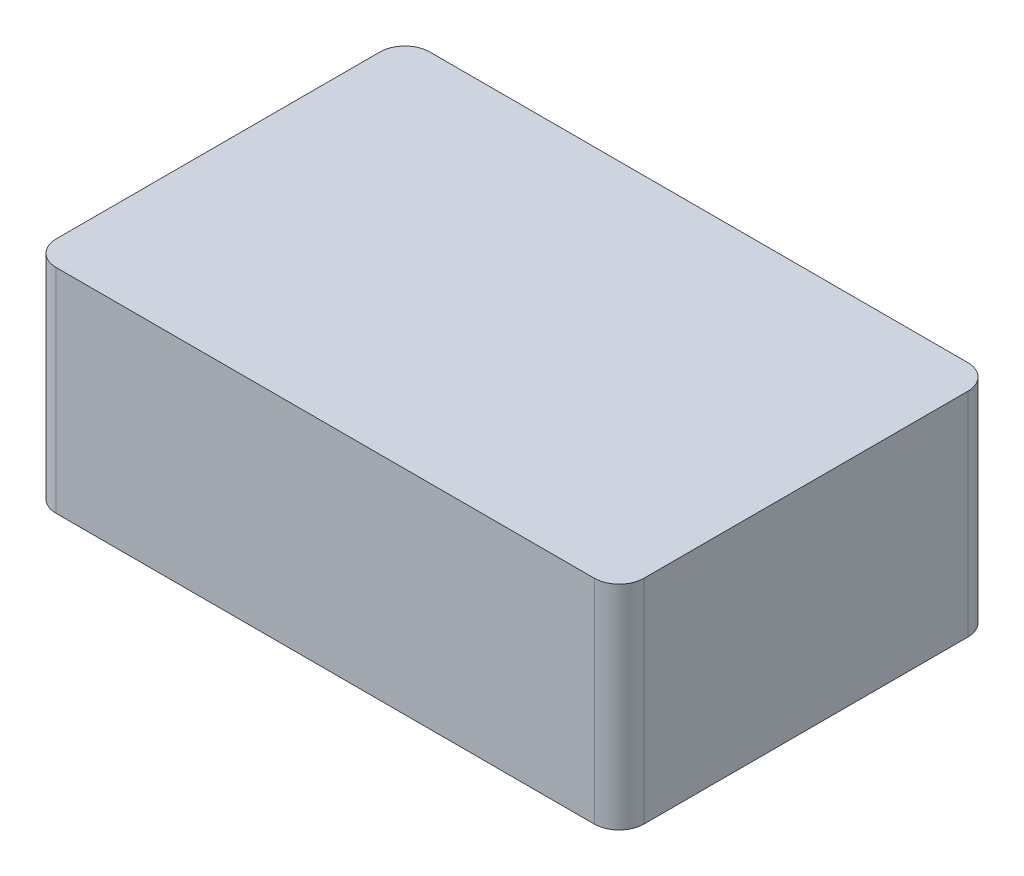
SolidWorks part; units mm, degrees
ref_plane "Alzado" through (0, 0, 0) normal (0, 0, 1) x (1, 0, 0)
ref_plane "Planta" through (0, 0, 0) normal (0, 1, 0) x (1, 0, 0)
ref_plane "Vista lateral" through (0, 0, 0) normal (1, 0, 0) x (0, 0, -1)
sketch "Croquis1" plane through (0, 0, 0) normal (0, 1, 0) x (1, 0, 0)
  line L1 (-43.75, 27.8) -> (43.75, 27.8)
  line L2 (-43.75, 27.8) -> (-43.75, -27.8)
  line L3 (-43.75, -27.8) -> (43.75, -27.8)
  line L4 (43.75, 27.8) -> (43.75, -27.8)
  line L5 (-43.75, 27.8) -> (43.75, -27.8) construction
  line L6 (-43.75, -27.8) -> (43.75, 27.8) construction
  point P0 (0, 0)
  dimension "D1" = 55.6
  dimension "D2" = 87.5
extrude "Saliente-Extruir1" add sketch "Croquis1" along normal blind 31.7
fillet "Redondeo1" radius 3.7 4 edges at (43.75, 15.85, 27.8) (43.75, 15.85, -27.8) (-43.75, 15.85, -27.8) (-43.75, 15.85, 27.8)
